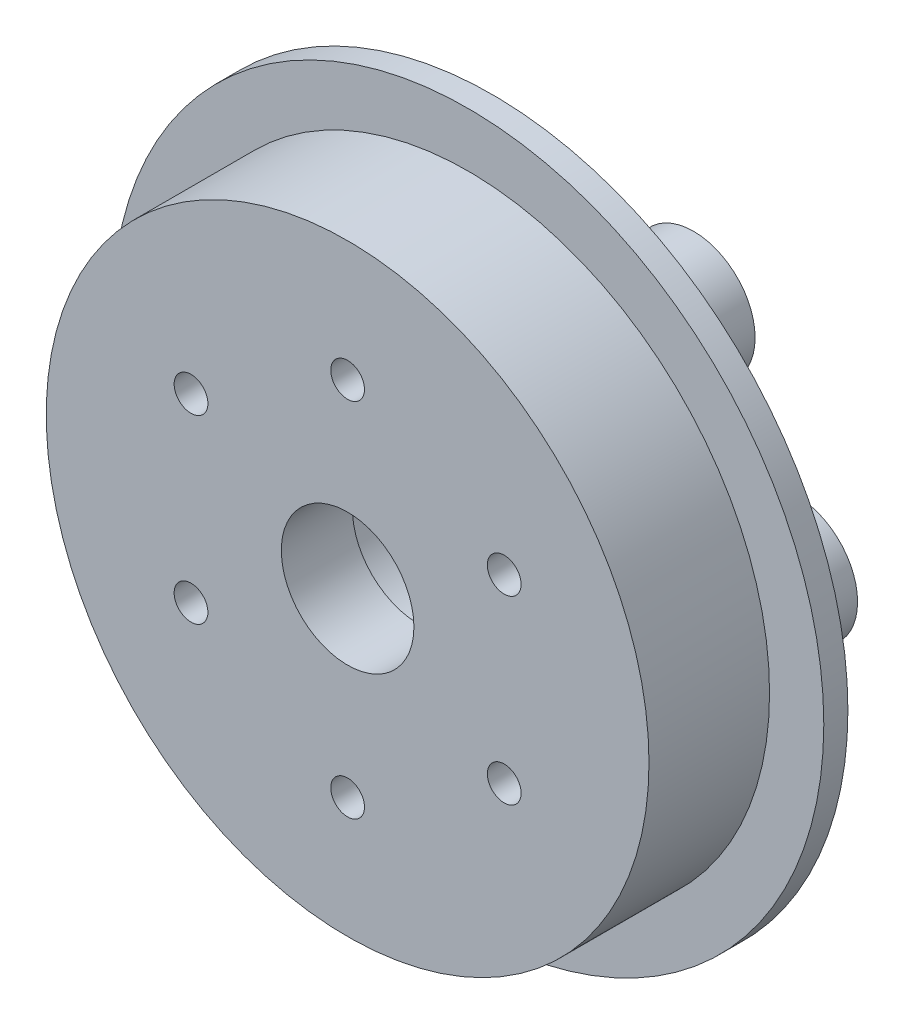
SolidWorks part; units mm, degrees
material "聚脂树脂"
ref_plane "前视基准面" through (0, 0, 0) normal (0, 0, 1) x (1, 0, 0)
ref_plane "上视基准面" through (0, 0, 0) normal (0, 1, 0) x (1, 0, 0)
ref_plane "右视基准面" through (0, 0, 0) normal (1, 0, 0) x (0, 0, -1)
sketch "草图2" plane through (0, 0, 0) normal (0, 0, 1) x (1, 0, 0)
  circle A0 centre (0, 0) radius 29.5
  dimension "D1" = 59
extrude "凸台-拉伸1" add sketch "草图2" along normal blind 2
sketch "草图3" plane through (0, 0, 2) normal (0, 0, 1) x (1, 0, 0)
  circle A0 centre (0, 0) radius 25
  dimension "D1" = 50
extrude "凸台-拉伸2" add sketch "草图3" along normal blind 10
sketch "草图4" plane through (0, 0, 0) normal (0, 0, -1) x (-1, 0, 0)
  line L0 (0, 0) -> (17, 0)
  circle A0 centre (17, 0) radius 5.1
  circle A3 centre (8.5, -14.7224) radius 5.1
  circle A5 centre (-8.5, -14.7224) radius 5.1
  circle A7 centre (-17, 0) radius 5.1
  circle A9 centre (-8.5, 14.7224) radius 5.1
  circle A11 centre (8.5, 14.7224) radius 5.1
  point P22 (0, 0)
  dimension "D2" = 10.2
  dimension "D1" = 17
  dimension "D4" = 6
extrude "凸台-拉伸3" add sketch "草图4" along normal blind 8.2
sketch "草图7" plane through (0, 0, 12) normal (0, 0, 1) x (1, 0, 0)
  line L0 (0, 0) -> (12.9904, 7.5)
  line L1 (0, 0) -> (17, 0)
  circle A0 centre (12.9904, 7.5) radius 1.4
  circle A2 centre (12.9904, -7.5) radius 1.4
  circle A3 centre (0, -15) radius 1.4
  circle A4 centre (-12.9904, -7.5) radius 1.4
  circle A5 centre (-12.9904, 7.5) radius 1.4
  circle A6 centre (0, 15) radius 1.4
  point P18 (0, 0)
  dimension "D4" = 2.8
  dimension "D1" = 30
  dimension "D2" = 15
  dimension "D3" = 6
extrude "切除-拉伸3" cut sketch "草图7" against normal blind 12
sketch "草图9" plane through (0, 0, 0) normal (0, 0, -1) x (-1, 0, 0)
  circle A0 centre (0, 0) radius 6.5
  dimension "D1" = 13
extrude "切除-拉伸4" cut sketch "草图9" against normal up to next
sketch "草图10" plane through (0, 0, 12) normal (0, 0, 1) x (1, 0, 0)
  circle A0 centre (0, 0) radius 5.5
  circle A1 centre (0, 0) radius 6.5 construction
  circle A2 centre (0, 0) radius 6.5
  dimension "D1" = 11
extrude "凸台-拉伸4" add sketch "草图10" against normal blind 5.9
